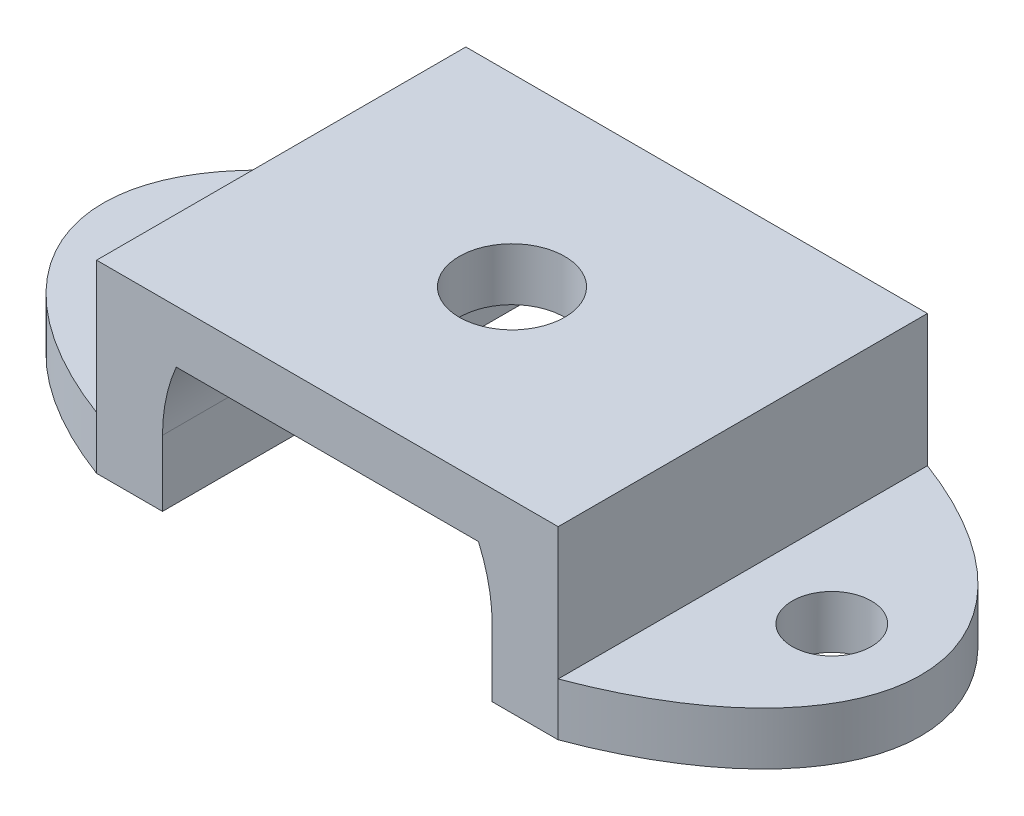
SolidWorks part; units mm, degrees
ref_plane "Plan de face" through (0, 0, 0) normal (0, 0, 1) x (1, 0, 0)
ref_plane "Plan de dessus" through (0, 0, 0) normal (0, 1, 0) x (1, 0, 0)
ref_plane "Plan de droite" through (0, 0, 0) normal (1, 0, 0) x (0, 0, -1)
sketch "Esquisse1" plane through (0, 0, 0) normal (0, 0, 1) x (1, 0, 0)
  line L0 (-15.5, 0) -> (-6.25, 0)
  line L1 (15.5, 0) -> (15.5, 2)
  line L2 (15.5, 2) -> (8.75, 2)
  line L3 (8.75, 2) -> (8.75, 7)
  line L4 (8.75, 7) -> (-8.75, 7)
  line L5 (-8.75, 7) -> (-8.75, 2)
  line L6 (-8.75, 2) -> (-15.5, 2)
  line L7 (-15.5, 2) -> (-15.5, 0)
  line L8 (-6.25, 2.5) -> (-6.25, 0)
  line L9 (-5.7282, 5) -> (5.7282, 5)
  line L10 (6.25, 0) -> (15.5, 0)
  line L11 (6.25, 2.5) -> (6.25, 0)
  line L12 (0, 5) -> (0, 0) construction
  arc A0 (-5.7282, 5) -> (-6.25, 2.5) centre (0, 2.5) ccw
  arc A1 (6.25, 2.5) -> (5.7282, 5) centre (0, 2.5) ccw
  dimension "D1" = 5
  dimension "D2" = 12.5
  dimension "D3" = 31
  dimension "D4" = 2
  dimension "D5" = 2.5
  dimension "D6" = 2
extrude "Boss.-Extru.1" add sketch "Esquisse1" along normal mid plane 14
sketch "Esquisse3" plane through (0, 2, 0) normal (0, 1, 0) x (1, 0, 0)
  line L0 (0, 0) -> (0, 11.5015) construction
  line L1 (-15.5, 7) -> (-8.75, -7) construction
  circle A0 centre (-12.125, 0) radius 1.5
  circle A1 centre (12.125, 0) radius 1.5
  dimension "D1" = 3
extrude "Enlèv. mat.-Extru.2" cut sketch "Esquisse3" against normal blind 8.5
sketch "Esquisse4" plane through (0, 7, 0) normal (0, 1, 0) x (1, 0, 0)
  circle A0 centre (0, 0) radius 2
  dimension "D1" = 4
extrude "Enlèv. mat.-Extru.3" cut sketch "Esquisse4" against normal through all
sketch "Esquisse5" plane through (0, 2, 0) normal (0, 1, 0) x (1, 0, 0)
  line L0 (15.5, -7) -> (15.5, 7) construction
  line L1 (-8.75, 7) -> (-15.5, 7) construction
  line L2 (-15.5, -7) -> (-15.5, 7) construction
  line L3 (-8.75, -7) -> (-15.5, -7) construction
  line L4 (15.5, -7) -> (8.75, -7) construction
  line L5 (15.5, 7) -> (8.75, 7) construction
  line L6 (-8.75, 7) -> (-15.5, 7)
  line L7 (-15.5, -7) -> (-15.5, 7)
  line L8 (-8.75, -7) -> (-15.5, -7)
  line L9 (15.5, -7) -> (8.75, -7)
  line L10 (15.5, -7) -> (15.5, 7)
  line L11 (15.5, 7) -> (8.75, 7)
  circle A2 centre (12.125, 0) radius 2.75 construction
  ellipse E0 centre (0, 0) end of major axis (15.5, 0) minor radius 8.4805
  dimension "D1" = 5.5
extrude "Enlèv. mat.-Extru.4" cut sketch "Esquisse5" against normal through all contours E0 L10 L1 | E0 L3 L4 | E0 L7 L8 | E0 L6 L7
